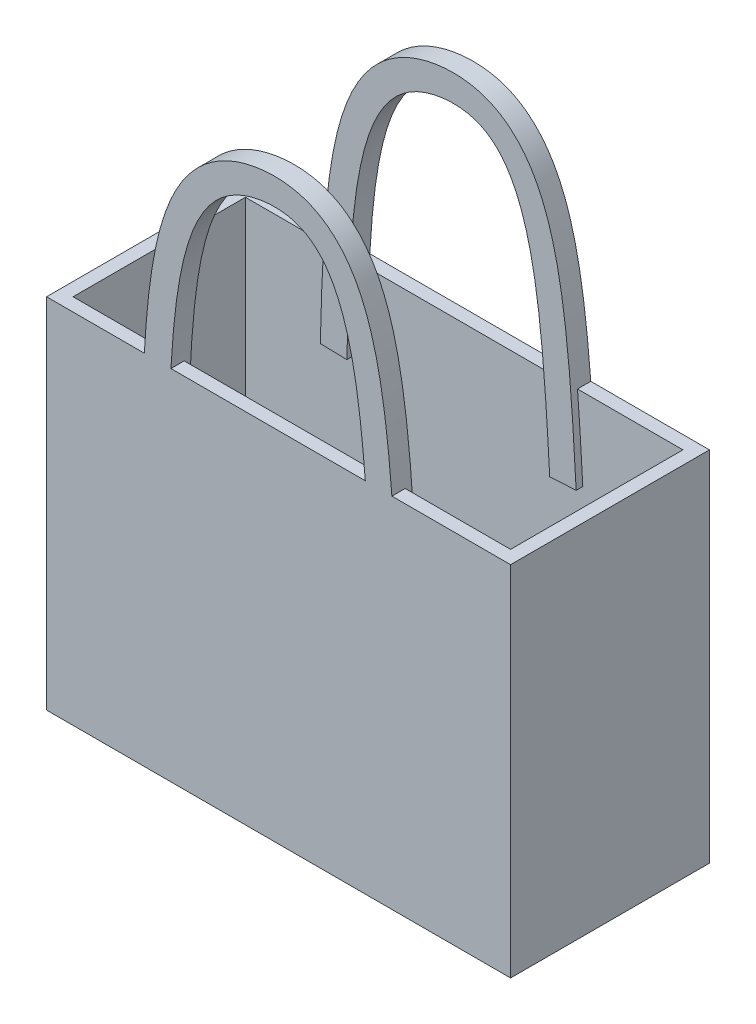
SolidWorks part; units mm, degrees
ref_plane "前视基准面" through (0, 0, 0) normal (0, 0, 1) x (1, 0, 0)
ref_plane "上视基准面" through (0, 0, 0) normal (0, 1, 0) x (1, 0, 0)
ref_plane "右视基准面" through (0, 0, 0) normal (1, 0, 0) x (0, 0, -1)
sketch "草图2" plane through (0, 0, 0) normal (0, 0, 1) x (1, 0, 0)
  line L1 (0, 0) -> (350, 0)
  line L2 (0, 0) -> (0, -270)
  line L3 (0, -270) -> (350, -270)
  line L4 (350, 0) -> (350, -270)
extrude "凸台-拉伸1" add sketch "草图2" along normal blind 150
ref_point "点2"
sketch "草图4" plane through (0, 0, 0) normal (0, 1, 0) x (1, 0, 0)
  line L0 (350, 0) -> (0, 0) construction
  line L5 (10, -10) -> (340, -10)
  line L6 (10, -10) -> (10, -140)
  line L7 (10, -140) -> (340, -140)
  line L8 (340, -10) -> (340, -140)
  line L9 (10, -10) -> (340, -140) construction
  line L10 (10, -140) -> (340, -10) construction
  line L11 (350, -150) -> (350, 0) construction
  point P0 (175, -75)
  dimension "D1" = 10
  dimension "D2" = 10
extrude "切除-拉伸1" cut sketch "草图4" against normal blind 231
ref_plane "基准面5" through (175, 0, 0) normal (1, 0, 0) x (0, 0, -1)
sketch "草图5" plane through (0, 0, 150) normal (0, 0, 1) x (1, 0, 0)
  line L0 (71.4991, -62.322) -> (91.493, -62.8156)
  line L1 (244.5056, -62.8156) -> (264.4746, -61.7018)
  spline S0 degree 3 poles (244.5056, -62.8156) (238.3215, 48.0567) (229.9361, 149.875) (99.6512, 140.5818) (94.1433, 44.5229) (91.493, -62.8156) knots 0 0 0 0 0.420288 0.520288 1 1 1 1
  spline S1 degree 1 poles (264.4746, -61.7018) (71.4991, -62.322) knots 0 0 1 1 construction
  spline S2 degree 3 poles (264.4746, -61.7018) (264.3599, -59.6451) (264.1282, -55.5183) (263.6626, -47.3715) (263.0687, -37.3189) (262.3261, -25.499) (261.2793, -10.0695) (259.8341, 8.5681) (257.7789, 29.8175) (255.2961, 49.8816) (251.254, 74.978) (245.8705, 97.5002) (238.3702, 117.3743) (231.3632, 130.9301) (222.5632, 142.9993) (211.5212, 153.1642) (200.4186, 159.3553) (190.637, 162.5867) (183.1589, 164.0889) (175.7155, 164.7885) (165.8582, 164.7866) (153.7923, 163.2135) (140.0183, 159.0567) (127.4885, 152.6483) (116.5044, 144.2031) (104.1174, 130.7144) (92.7079, 110.6547) (83.759, 82.8739) (78.9917, 56.7813) (76.3073, 34.2021) (74.7611, 16.4395) (73.59, -2.1217) (72.8556, -18.225) (72.3721, -31.4691) (72.0515, -41.5764) (71.8111, -50.1433) (71.6301, -57.0721) (71.5422, -60.5752) (71.4991, -62.322) knots 0 0 0 0 0.007812 0.015625 0.03125 0.046875 0.0625 0.09375 0.125 0.15625 0.1875 0.25 0.28125 0.3125 0.34375 0.375 0.40625 0.421875 0.4375 0.453125 0.46875 0.5 0.53125 0.5625 0.59375 0.625 0.6875 0.75 0.8125 0.84375 0.875 0.90625 0.9375 0.953125 0.96875 0.984375 0.992188 1 1 1 1
  dimension "D1" = 20
extrude "凸台-拉伸2" add sketch "草图5" against normal blind 15
ref_plane "基准面6" through (0, 0, 75) normal (0, 0, -1) x (-1, 0, 0)
mirror "镜向1" about plane through (0, 0, 75) normal (0, 0, -1) of "凸台-拉伸2"
